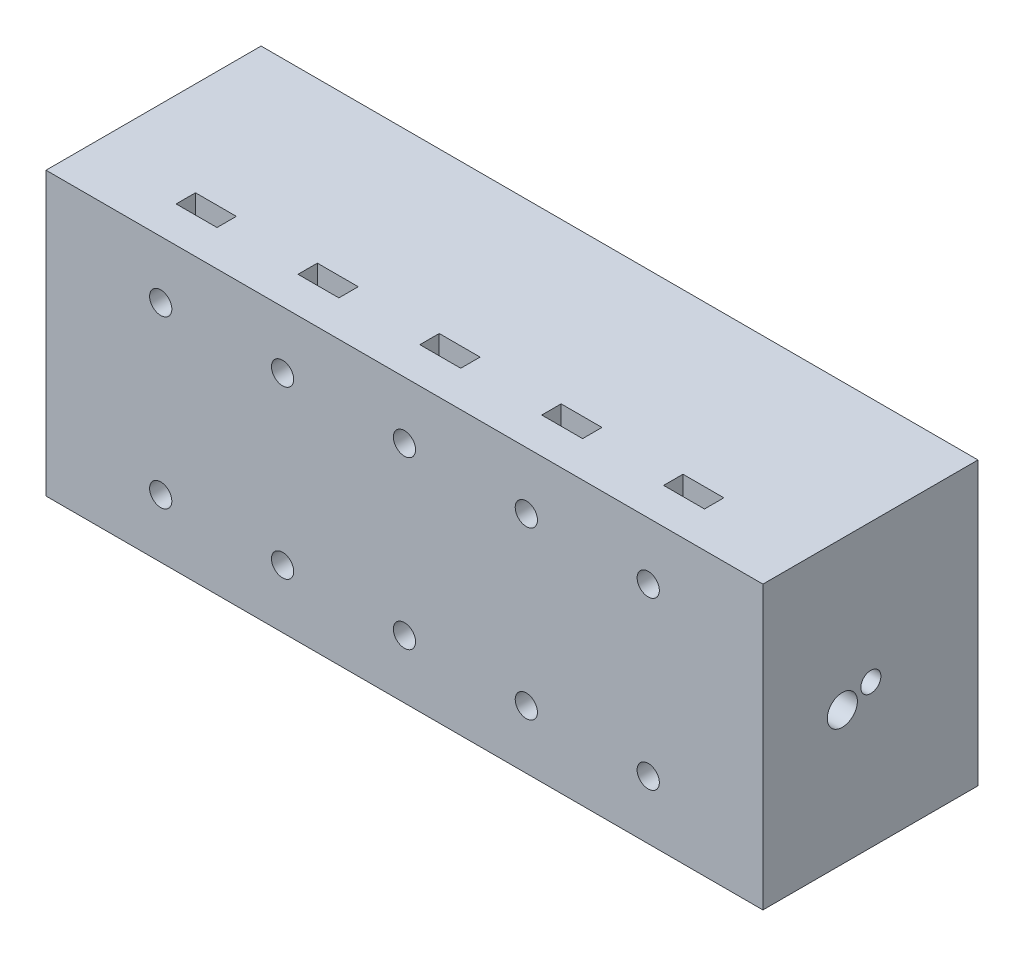
SolidWorks part; units mm, degrees
ref_plane "Ebene vorne" through (0, 0, 0) normal (0, 0, 1) x (1, 0, 0)
ref_plane "Ebene oben" through (0, 0, 0) normal (0, 1, 0) x (1, 0, 0)
ref_plane "Ebene rechts" through (0, 0, 0) normal (1, 0, 0) x (0, 0, -1)
sketch "Skizze2" plane through (0, 0, 0) normal (0, 0, 1) x (1, 0, 0)
  line L1 (0, 0) -> (100, 0)
  line L2 (0, 0) -> (0, 39.3642)
  line L3 (0, 39.3642) -> (100, 39.3642)
  line L4 (100, 0) -> (100, 39.3642)
  dimension "D1" = 39.3642
  dimension "D2" = 100
extrude "Aufsatz-Linear austragen1" add sketch "Skizze2" along normal blind 30
sketch "Skizze3" plane through (0, 0, 30) normal (0, 0, 1) x (1, 0, 0)
  line L0 (0, 19.6821) -> (100, 19.6821) construction
  line L1 (0, 39.3642) -> (0, 0) construction
  line L2 (100, 0) -> (100, 39.3642) construction
ref_plane "Ebene2" through (0, 19.7642, 0) normal (0, 1, 0) x (1, 0, 0)
sketch "Skizze9" plane through (0, 0, 30) normal (0, 0, 1) x (1, 0, 0)
  line L0 (50, 0) -> (50, 39.3642) construction
  line L1 (0, 0) -> (100, 0) construction
  line L2 (100, 39.3642) -> (0, 39.3642) construction
ref_plane "Ebene3" through (50, 0, 0) normal (-1, 0, 0) x (0, 0, 1)
sketch "Skizze10" plane through (50, 0, 0) normal (-1, 0, 0) x (0, 0, 1)
  line L0 (14.9458, 42.0451) -> (14.9458, -1.991) construction
  line L1 (-1.6741, 19.9497) -> (31.3778, 19.9497) construction
  circle A0 centre (14.9458, 20.027) radius 5
  dimension "D1" = 10
extrude "Schnitt-Linear austragen1" cut sketch "Skizze10" against normal blind 40 and the other way blind 40
ref_plane "Ebene4" through (90, 0, 0) normal (-1, 0, 0) x (0, 0, 1)
ref_plane "Ebene5" through (10, 0, 0) normal (-1, 0, 0) x (0, 0, 1)
sketch "Skizze17" plane through (90, 0, 0) normal (-1, 0, 0) x (0, 0, 1)
  circle A0 centre (14.9458, 20.027) radius 1.4
  dimension "D1" = 2.8
extrude "Schnitt-Linear austragen2" cut sketch "Skizze17" against normal through all
mirror "Spiegeln1" about plane through (50, 0, 0) normal (-1, 0, 0) of "Schnitt-Linear austragen2"
sketch "Skizze18" plane through (0, 39.3642, 0) normal (0, 1, 0) x (1, 0, 0)
  line L0 (100, -15) -> (0, -15) construction
  line L1 (100, -30) -> (100, 0) construction
ref_plane "Ebene6" through (0, 0, 15) normal (0, 0, -1) x (-1, 0, 0)
sketch "Skizze24" plane through (0, 0, 30) normal (0, 0, 1) x (1, 0, 0)
  line L0 (0, 39.3642) -> (0, 0) construction
  line L1 (100, 39.3642) -> (0, 39.3642) construction
  line L4 (100, 0) -> (100, 39.3642) construction
  circle A0 centre (16, 31.3642) radius 1.55
  circle A1 centre (33, 31.3642) radius 1.55
  circle A2 centre (50, 31.3642) radius 1.55
  circle A3 centre (67, 31.3642) radius 1.55
  circle A4 centre (84, 31.3642) radius 1.55
  dimension "D1" = 3.1
  dimension "D4" = 3.1
  dimension "D5" = 3.1
  dimension "D6" = 3.1
  dimension "D7" = 3.1
  dimension "D2" = 16
  dimension "D3" = 8
  dimension "D8" = 17
  dimension "D9" = 17
  dimension "D10" = 17
  dimension "D11" = 17
  dimension "D12" = 16
extrude "Schnitt-Linear austragen4" cut sketch "Skizze24" against normal through all
sketch "Skizze22" plane through (0, 0, 0) normal (-1, 0, 0) x (0, 0, 1)
  line L0 (30, 39.3642) -> (0, 39.3642) construction
  line L1 (0, 0) -> (15, 0)
  line L2 (0, 0) -> (0, 39.3642)
  line L3 (0, 39.3642) -> (15, 39.3642)
ref_plane "Ebene7" through (0, 0, 8.4) normal (0, 0, -1) x (-1, 0, 0)
ref_plane "Ebene8" through (16, 0, 0) normal (-1, 0, 0) x (0, 0, 1)
sketch "Skizze35" plane through (0, 0, 30) normal (0, 0, 1) x (1, 0, 0)
  line L0 (89.9018, 21.3451) -> (89.9018, 39.3769) construction
  line L1 (89.9018, 39.3769) -> (89.9018, 0) construction
  line L2 (0, 0) -> (100, 0) construction
ref_plane "Ebene9" through (90, 0, 0) normal (1, 0, 0) x (0, 0, -1)
sketch "Skizze36" plane through (90, 0, 0) normal (1, 0, 0) x (0, 0, -1)
  line L0 (-20.1004, 18.2046) -> (-18.9246, 18.6336)
  circle A0 centre (-18.9246, 18.6336) radius 0.75
  point P3 (-19.5125, 18.4191)
  dimension "D1" = 1.5
sketch "Skizze37" plane through (100, 0, 0) normal (1, 0, 0) x (0, 0, -1)
  circle A0 centre (-18.9246, 18.6336) radius 0.7369
extrude "Schnitt-Linear austragen9" cut sketch "Skizze37" against normal through all
sketch "Skizze40" plane through (100, 0, 0) normal (1, 0, 0) x (0, 0, -1)
  circle A0 centre (-18.9246, 18.6336) radius 2.1
  dimension "D1" = 4.2
extrude "Schnitt-Linear austragen10" cut sketch "Skizze40" against normal blind 6
sketch "Skizze42" plane through (0, 0, 0) normal (-1, 0, 0) x (0, 0, 1)
  line L0 (10.1439, 18.6336) -> (10.8642, 18.8426) construction
  circle A0 centre (14.9458, 20.027) radius 5 construction
  circle A1 centre (10.8642, 18.8426) radius 0.75
  dimension "D1" = 0.75
extrude "Schnitt-Linear austragen12" cut sketch "Skizze42" against normal blind 10
fillet "Verrundung1" radius 1 1 edges at (94, 18.6336, 18.1877)
sketch "Skizze46" plane through (0, 0, 0) normal (0, 0, -1) x (-1, 0, 0)
  circle A0 centre (-84, 31.3642) radius 2.85
  dimension "D1" = 5.7
extrude "Schnitt-Linear austragen15" cut sketch "Skizze46" against normal blind 10
sketch "Skizze50" plane through (0, 0, 30) normal (0, 0, 1) x (1, 0, 0)
  line L0 (81.15, 33.0096) -> (81.15, 39.3642)
  line L2 (81.15, 33.0096) -> (81.15, 29.7187)
  line L3 (81.15, 29.7187) -> (84, 28.0733)
  line L4 (84, 28.0733) -> (86.85, 29.7187)
  line L5 (86.85, 29.7187) -> (86.85, 33.0096)
  line L7 (100, 39.3642) -> (0, 39.3642) construction
  line L8 (81.15, 39.3642) -> (86.85, 39.3642)
  line L9 (86.85, 39.3642) -> (86.85, 33.0096)
  line L11 (84, 34.6551) -> (81.15, 33.0096) [skipped]
  line L12 (86.85, 33.0096) -> (84, 34.6551) [skipped]
  circle A0 centre (84, 31.3642) radius 2.85 construction
  dimension "D1" = 5.7
extrude "Schnitt-Linear austragen25" cut sketch "Skizze50" against normal blind 2.7 from offset 5 offset against normal yes
pattern_linear "Lineares Muster1" count 5 spacing 17 along (-1, 0, 0) of "Schnitt-Linear austragen25", "Schnitt-Linear austragen15"
mirror "Spiegeln2" about plane through (0, 19.7642, 0) normal (0, 1, 0) of "Lineares Muster1", "Schnitt-Linear austragen15", "Schnitt-Linear austragen25"
mirror "Spiegeln3" about plane through (0, 19.7642, 0) normal (0, 1, 0) of "Schnitt-Linear austragen4"
sketch "Skizze51" plane through (0, 0, 30) normal (0, 0, 1) x (1, 0, 0)
  line L0 (100, 0) -> (100, 39.3642) construction
  line L1 (0, 0) -> (100, 0) construction
  line L2 (0, 0) -> (0, 39.3642) construction
  line L3 (100, 39.3642) -> (0, 39.3642) construction
  circle A0 centre (5, 34.3642) radius 1.55
  circle A1 centre (95, 5) radius 1.55
  dimension "D1" = 3.1
  dimension "D2" = 3.1
  dimension "D3" = 5
  dimension "D4" = 5
  dimension "D5" = 5
  dimension "D6" = 5
extrude "Schnitt-Linear austragen26" cut sketch "Skizze51" against normal blind 10 from offset 10 offset against normal yes
